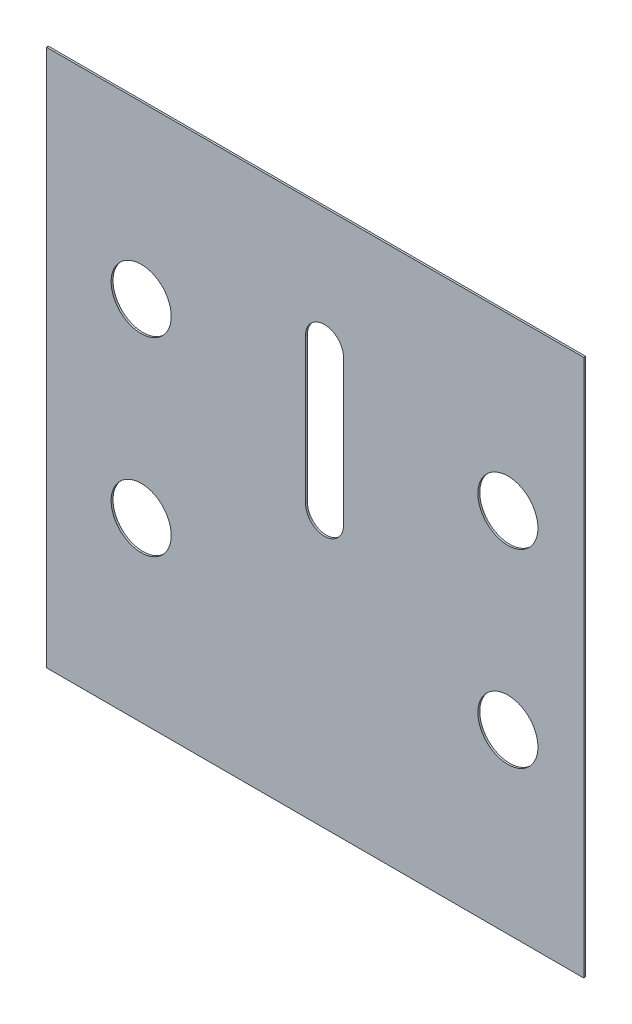
SolidWorks part; units mm, degrees
ref_plane "Front Plane" through (0, 0, 0) normal (0, 0, 1) x (1, 0, 0)
ref_plane "Top Plane" through (0, 0, 0) normal (0, 1, 0) x (1, 0, 0)
ref_plane "Right Plane" through (0, 0, 0) normal (1, 0, 0) x (0, 0, -1)
sketch "草图1" plane through (0, 0, 0) normal (0, 0, 1) x (1, 0, 0)
  line L1 (0, 850) -> (850, 850)
  line L2 (0, 850) -> (0, 0)
  line L3 (0, 0) -> (850, 0)
  line L4 (850, 850) -> (850, 0)
extrude "凸台-拉伸1" add sketch "草图1" along normal blind 3
sketch "草图2" plane through (0, 0, 3) normal (0, 0, 1) x (1, 0, 0)
  line L1 (440, 660) -> (440, 430) construction
  line L2 (470, 660) -> (470, 430)
  line L3 (410, 660) -> (410, 430)
  circle A0 centre (150, 580) radius 47.5
  circle A1 centre (150, 280) radius 47.5
  circle A2 centre (730, 280) radius 47.5
  circle A3 centre (730, 580) radius 47.5
  arc A4 (470, 660) -> (410, 660) centre (440, 660) ccw
  arc A5 (410, 430) -> (470, 430) centre (440, 430) ccw
  point P16 (440, 545)
  dimension "D1" = 95
  dimension "D2" = 95
  dimension "D3" = 95
  dimension "D4" = 95
  dimension "D5" = 30
extrude "切除-拉伸1" cut sketch "草图2" against normal through all
